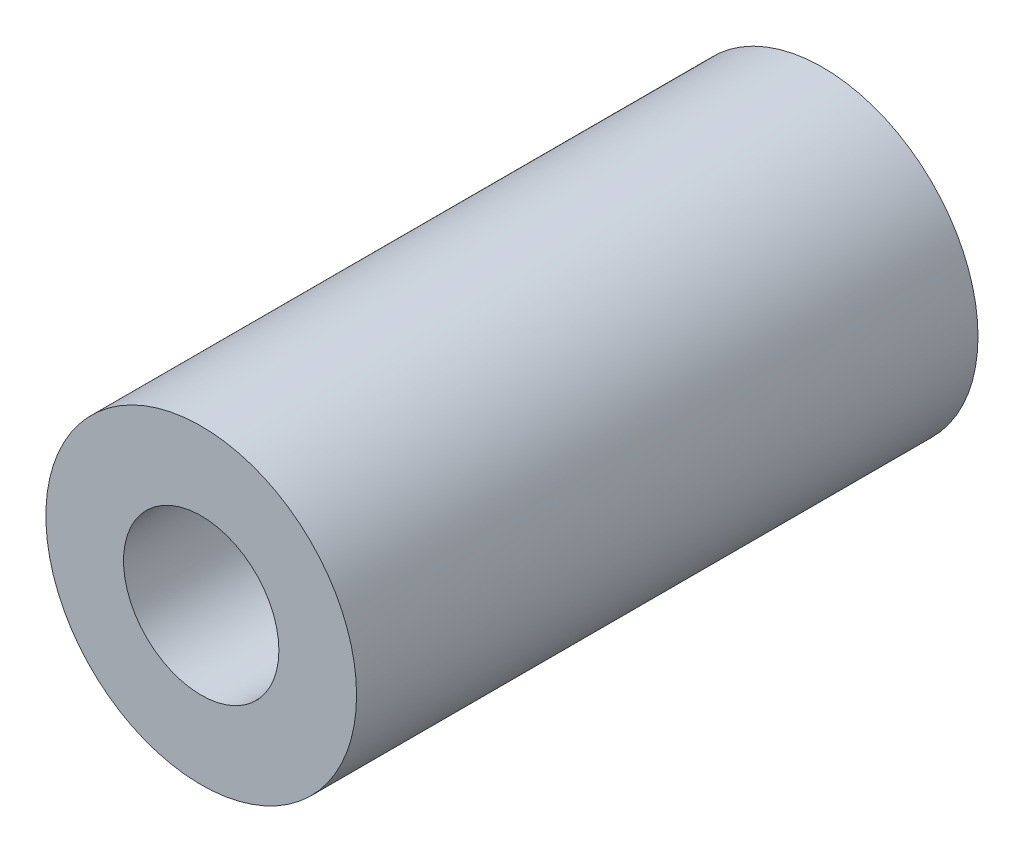
SolidWorks part; units mm, degrees
ref_plane "前视基准面" through (0, 0, 0) normal (0, 0, 1) x (1, 0, 0)
ref_plane "上视基准面" through (0, 0, 0) normal (0, 1, 0) x (1, 0, 0)
ref_plane "右视基准面" through (0, 0, 0) normal (1, 0, 0) x (0, 0, -1)
sketch "草图1" plane through (0, 0, 0) normal (0, 0, 1) x (1, 0, 0)
  circle A0 centre (0, 0) radius 2
  circle A1 centre (0, 0) radius 1
extrude "凸台-拉伸1" add sketch "草图1" along normal blind 8
